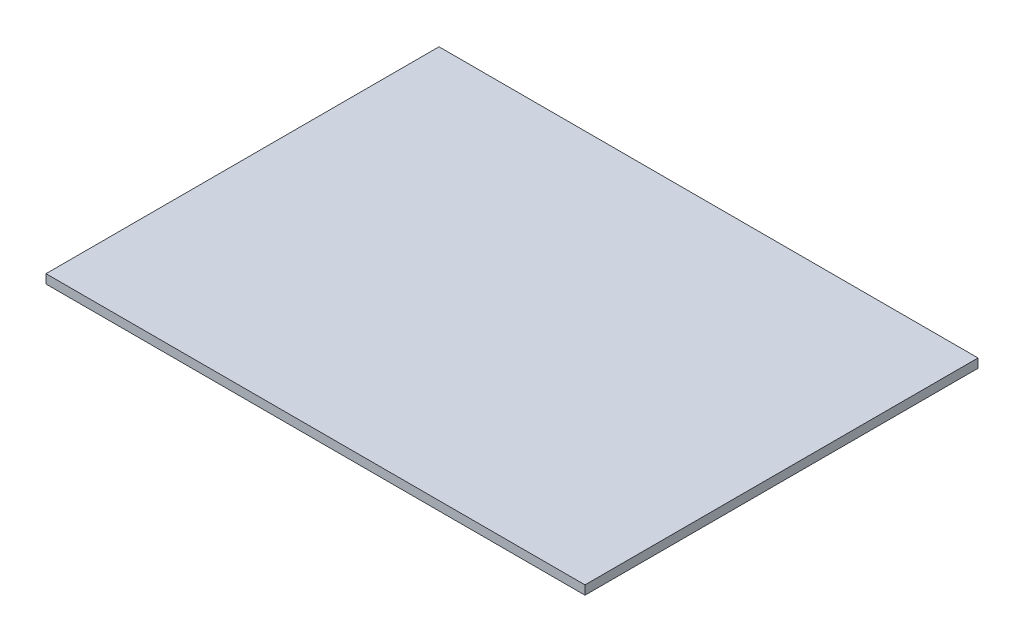
SolidWorks part; units mm, degrees
material "未指定"
ref_plane "正面" through (0, 0, 0) normal (0, 0, 1) x (1, 0, 0)
ref_plane "平面" through (0, 0, 0) normal (0, 1, 0) x (1, 0, 0)
ref_plane "右側面" through (0, 0, 0) normal (1, 0, 0) x (0, 0, -1)
sketch "ｽｹｯﾁ1" plane through (0, 0, 0) normal (0, 1, 0) x (1, 0, 0)
  line L0 (0, 35) -> (96, 35)
  line L1 (96, 35) -> (96, -35)
  line L2 (96, -35) -> (0, -35)
  line L3 (0, -35) -> (0, 35)
  line L4 (0, 0) -> (25, 0) construction
  dimension "D1" = 96
  dimension "D2" = 70
extrude "基板" add sketch "ｽｹｯﾁ1" along normal mid plane 1.6
equation "\"BPB_LEN\" = 96"
equation "\"D1@ｽｹｯﾁ1\" = \"BPB_LEN\""
equation "\"BPB_W\" = 70"
equation "\"D2@ｽｹｯﾁ1\" = \"BPB_W\""
equation "\"PCB_T\" = 1.6"
equation "\"D1@基板\" = \"PCB_T\""
